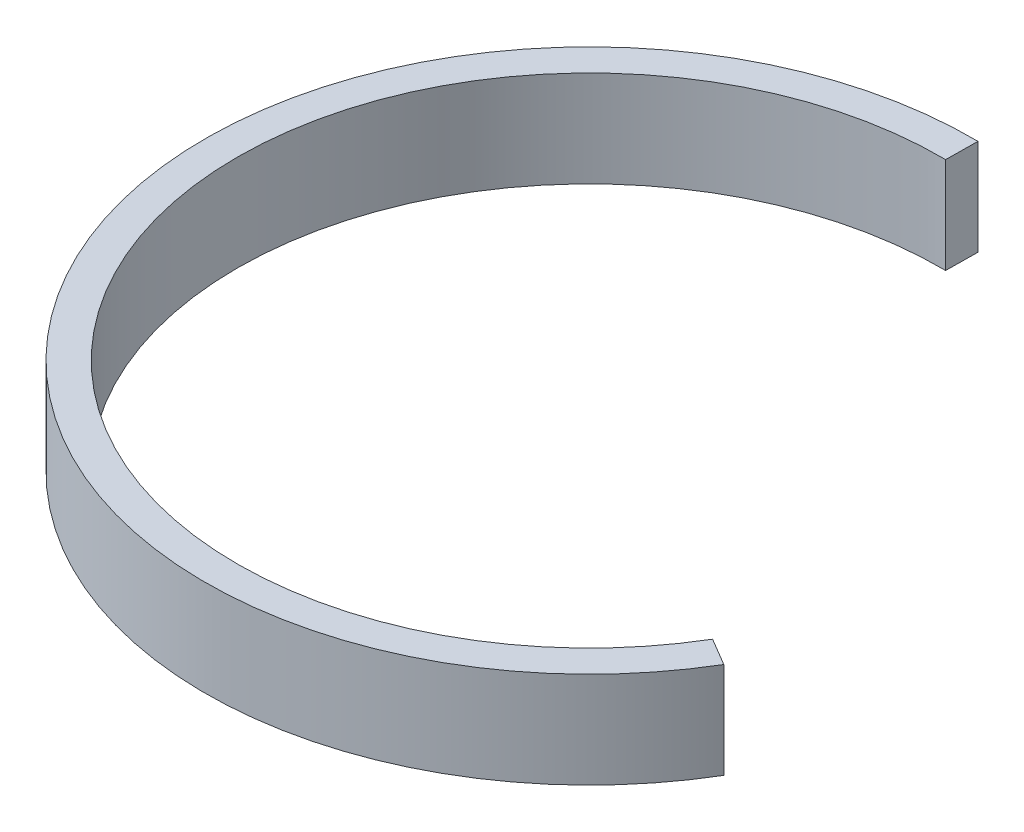
SolidWorks part; units mm, degrees
ref_plane "Front Plane" through (0, 0, 0) normal (0, 0, 1) x (1, 0, 0)
ref_plane "Top Plane" through (0, 0, 0) normal (0, 1, 0) x (1, 0, 0)
ref_plane "Right Plane" through (0, 0, 0) normal (1, 0, 0) x (0, 0, -1)
sketch "Sketch1" plane through (0, 0, 0) normal (0, 1, 0) x (1, 0, 0)
  line L0 (1.2876, 109.9925) -> (1.4046, 119.9918)
  line L2 (103.2136, -61.2123) -> (94.6125, -56.1113)
  arc A0 (1.2876, 109.9925) -> (94.6125, -56.1113) centre (0, 0) ccw
  arc A1 (1.4046, 119.9918) -> (103.2136, -61.2123) centre (0, 0) ccw
  dimension "D1" = 220
  dimension "D2" = 10
  dimension "D3" = 120
extrude "Boss-Extrude1" add sketch "Sketch1" along normal blind 30
